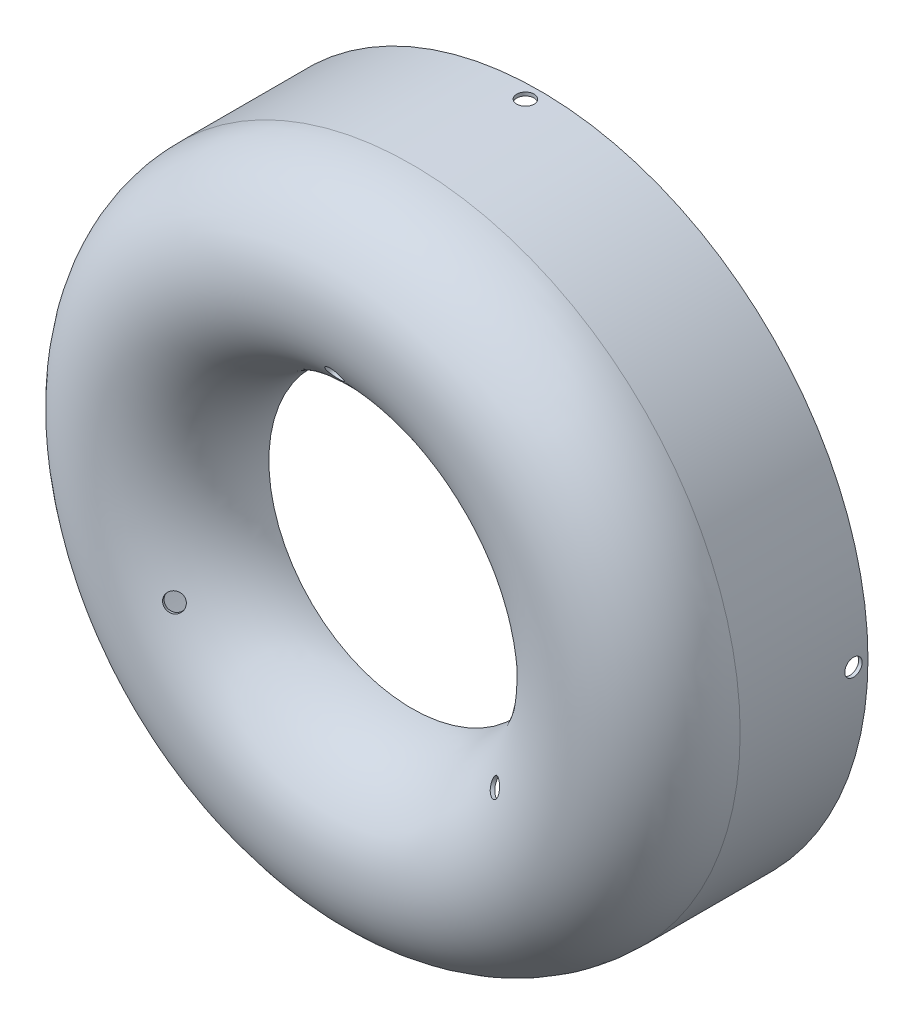
SolidWorks part; units mm, degrees
ref_plane "Plan1" through (0, 0, 0) normal (0, 0, 1) x (1, 0, 0)
ref_plane "Plan2" through (0, 0, 0) normal (0, 1, 0) x (1, 0, 0)
ref_plane "Plan3" through (0, 0, 0) normal (1, 0, 0) x (0, 0, -1)
sketch "Esquisse1" plane through (0, 0, 0) normal (1, 0, 0) x (0, 0, -1)
  line L0 (-53.0037, 0) -> (108.2275, 0) construction
  line L1 (0, 56.6) -> (-22.05, 56.6)
  line L2 (0, 56) -> (-22.05, 56)
  line L3 (0, 56.6) -> (0, 56)
  line L4 (-22.05, 25.3) -> (-22.05, 24.7)
  arc A0 (-22.05, 56.6) -> (-22.05, 24.7) centre (-22.05, 40.65) ccw
  arc A1 (-22.05, 56) -> (-22.05, 25.3) centre (-22.05, 40.65) ccw
  dimension "D1" = 38
  dimension "D2" = 112
  dimension "D4" = 50.6
  dimension "D3" = 0.6
revolve "Base-Révolution" add sketch "Esquisse1" angle 360 about L0
sketch "Esquisse2" plane through (0, 0, 0) normal (0, 1, 0) x (1, 0, 0)
  line L0 (0, -53.0037) -> (0, 108.2275) construction
  circle A0 centre (0, -2.5) radius 1.5
  dimension "D1" = 3
  dimension "D2" = 2.5
extrude "Enlèv. mat.-Extru.1" cut sketch "Esquisse2" against normal through all
pattern_circular "Répétition circulaire1" count 4 over 360 about axis through (0, 0, 53.0037) along (0, 0, -1) of "Enlèv. mat.-Extru.1"
ref_plane "Plan4" through (0, 57, 0) normal (0, 1, 0) x (-1, 0, 0)
ref_plane "Plan5" through (0, 0, 0) normal (0.342, 0.9397, 0) x (-0.9397, 0.342, 0)
sketch "Esquisse4" plane through (0, 0, 0) normal (0.342, 0.9397, 0) x (-0.9397, 0.342, 0)
  line L0 (0, 25.2803) -> (0, 20) construction
  point P9 (0, 0)
ref_plane "Plan6" through (0, 0, 0) normal (-0.1736, 0.9848, 0) x (-0.9848, -0.1736, 0)
sketch "Esquisse6" plane through (0, -7.4147, 12.8427) normal (0, 0.5, -0.866) x (-1, 0, 0)
  circle A0 centre (0, 45.3564) radius 1.5
  circle A1 centre (0, 45.3564) radius 2.5 construction
  dimension "D1" = 3
extrude "Enlèv. mat.-Extru.5" cut sketch "Esquisse6" along normal blind 3
pattern_circular "Répétition circulaire4" count 3 over 360 about axis through (0, 0, 53.0037) along (0, 0, -1) of "Enlèv. mat.-Extru.5"
